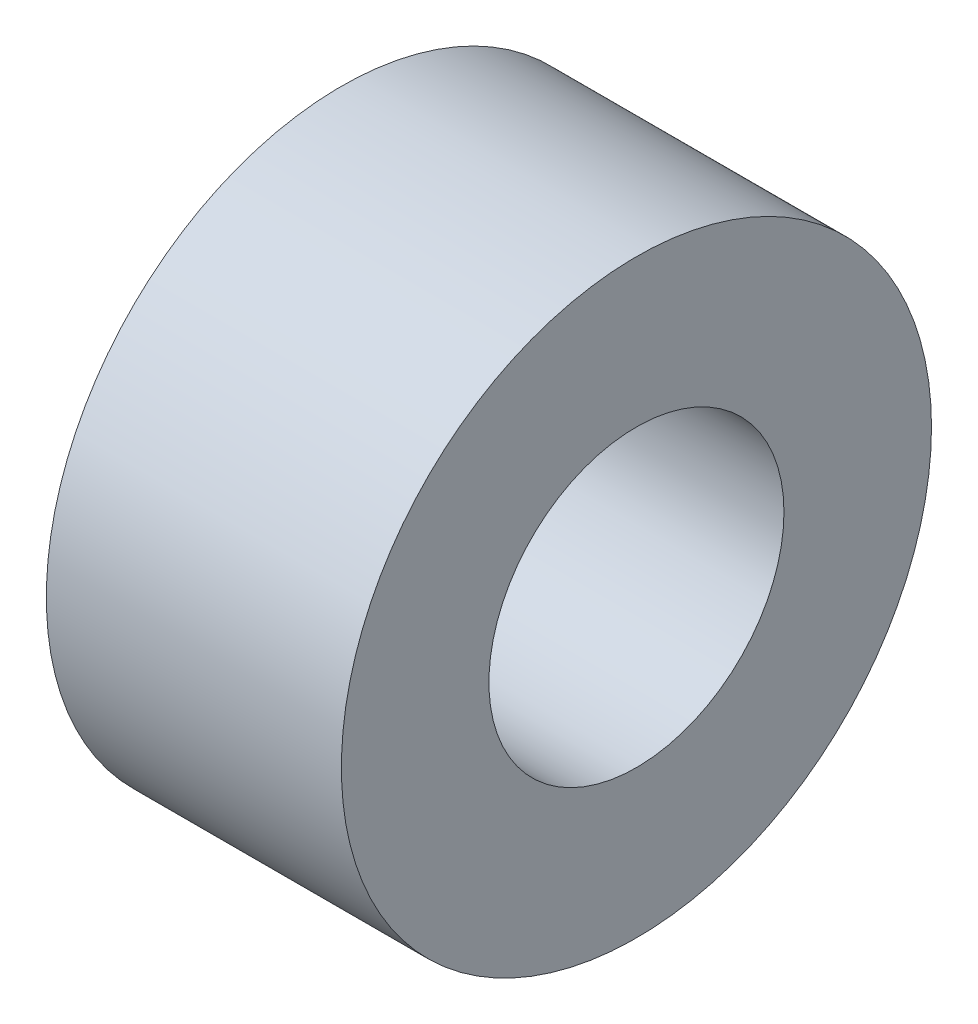
SolidWorks part; units mm, degrees
material "CMR DEFAULT - CHANGE MATERIAL"
ref_plane "XY PLANE - TOP" through (0, 0, 0) normal (0, 0, 1) x (1, 0, 0)
ref_plane "XZ PLANE - SIDE" through (0, 0, 0) normal (0, 1, 0) x (1, 0, 0)
ref_plane "YZ PLANE - FRONT" through (0, 0, 0) normal (1, 0, 0) x (0, 0, -1)
sketch "Sketch1" plane through (0, 0, 0) normal (1, 0, 0) x (0, 0, -1)
  circle A0 centre (0, 0) radius 6.35
  circle A1 centre (0, 0) radius 3.175
  dimension "D1" = 12.7
  dimension "D2" = 6.35
extrude "Boss-Extrude1" add sketch "Sketch1" along normal blind 6.35
